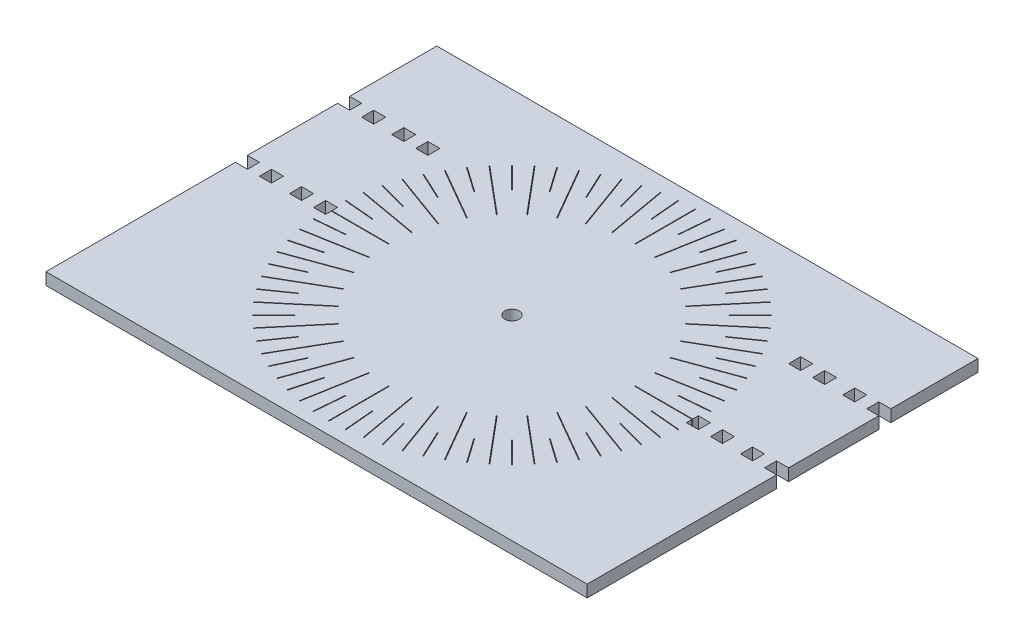
SolidWorks part; units mm, degrees
ref_plane "Front Plane" through (0, 0, 0) normal (0, 0, 1) x (1, 0, 0)
ref_plane "Top Plane" through (0, 0, 0) normal (0, 1, 0) x (1, 0, 0)
ref_plane "Right Plane" through (0, 0, 0) normal (1, 0, 0) x (0, 0, -1)
sketch "Sketch1" plane through (0, 0, 0) normal (0, 1, 0) x (1, 0, 0)
  line L0 (13.3728, 67.8735) -> (13.3728, -97.2265) construction
  line L1 (-100.9272, 67.8735) -> (127.6728, 67.8735)
  line L2 (-100.9272, 67.8735) -> (-100.9272, -97.2265)
  line L3 (-100.9272, -97.2265) -> (127.6728, -97.2265)
  line L4 (127.6728, 67.8735) -> (127.6728, -97.2265)
  line L5 (-100.9272, -14.6765) -> (127.6728, -14.6765) construction
  line L6 (-100.9272, -17.2165) -> (127.6728, -17.2165) construction
  line L7 (-100.9272, -12.1365) -> (127.6728, -12.1365) construction
  line L8 (-81.8772, 67.8735) -> (-81.8772, -97.2265) construction
  line L9 (108.6228, 67.8735) -> (108.6228, -97.2265) construction
  line L10 (-100.9272, 6.9135) -> (127.6728, 6.9135) construction
  line L11 (89.5728, -12.1365) -> (89.5728, -17.2165)
  line L12 (112.4328, -12.1365) -> (117.5128, -12.1365)
  line L13 (112.4328, -12.1365) -> (112.4328, -17.2165)
  line L14 (112.4328, -17.2165) -> (117.5128, -17.2165)
  line L15 (117.5128, -12.1365) -> (117.5128, -17.2165)
  line L16 (122.5928, -12.1365) -> (127.6728, -12.1365)
  line L17 (122.5928, -12.1365) -> (122.5928, -17.2165)
  line L18 (122.5928, -17.2165) -> (127.6728, -17.2165)
  line L19 (127.6728, -12.1365) -> (127.6728, -17.2165)
  line L20 (94.6528, -17.2165) -> (89.5728, -17.2165)
  line L21 (94.6528, -12.1365) -> (94.6528, -17.2165)
  line L22 (94.6528, -12.1365) -> (89.5728, -12.1365)
  line L23 (99.7328, -12.1365) -> (99.7328, -17.2165)
  line L24 (104.8128, -17.2165) -> (99.7328, -17.2165)
  line L25 (104.8128, -12.1365) -> (104.8128, -17.2165)
  line L26 (104.8128, -12.1365) -> (99.7328, -12.1365)
  line L27 (104.8128, 25.9635) -> (99.7328, 25.9635)
  line L28 (104.8128, 25.9635) -> (104.8128, 31.0435)
  line L29 (104.8128, 31.0435) -> (99.7328, 31.0435)
  line L30 (99.7328, 25.9635) -> (99.7328, 31.0435)
  line L31 (94.6528, 25.9635) -> (89.5728, 25.9635)
  line L32 (94.6528, 25.9635) -> (94.6528, 31.0435)
  line L33 (94.6528, 31.0435) -> (89.5728, 31.0435)
  line L34 (127.6728, 25.9635) -> (127.6728, 31.0435)
  line L35 (122.5928, 31.0435) -> (127.6728, 31.0435)
  line L36 (122.5928, 25.9635) -> (122.5928, 31.0435)
  line L37 (122.5928, 25.9635) -> (127.6728, 25.9635)
  line L38 (117.5128, 25.9635) -> (117.5128, 31.0435)
  line L39 (112.4328, 31.0435) -> (117.5128, 31.0435)
  line L40 (112.4328, 25.9635) -> (112.4328, 31.0435)
  line L41 (112.4328, 25.9635) -> (117.5128, 25.9635)
  line L42 (89.5728, 25.9635) -> (89.5728, 31.0435)
  line L43 (-78.0672, -12.1365) -> (-78.0672, -17.2165)
  line L44 (-100.9272, -12.1365) -> (-95.8472, -12.1365)
  line L45 (-100.9272, -12.1365) -> (-100.9272, -17.2165)
  line L46 (-100.9272, -17.2165) -> (-95.8472, -17.2165)
  line L47 (-95.8472, -12.1365) -> (-95.8472, -17.2165)
  line L48 (-90.7672, -12.1365) -> (-85.6872, -12.1365)
  line L49 (-90.7672, -12.1365) -> (-90.7672, -17.2165)
  line L50 (-90.7672, -17.2165) -> (-85.6872, -17.2165)
  line L51 (-85.6872, -12.1365) -> (-85.6872, -17.2165)
  line L52 (-72.9872, -17.2165) -> (-78.0672, -17.2165)
  line L53 (-72.9872, -12.1365) -> (-72.9872, -17.2165)
  line L54 (-72.9872, -12.1365) -> (-78.0672, -12.1365)
  line L55 (-67.9072, -12.1365) -> (-67.9072, -17.2165)
  line L56 (-62.8272, -17.2165) -> (-67.9072, -17.2165)
  line L57 (-62.8272, -12.1365) -> (-62.8272, -17.2165)
  line L58 (-62.8272, -12.1365) -> (-67.9072, -12.1365)
  line L59 (-62.8272, 25.9635) -> (-67.9072, 25.9635)
  line L60 (-62.8272, 25.9635) -> (-62.8272, 31.0435)
  line L61 (-62.8272, 31.0435) -> (-67.9072, 31.0435)
  line L62 (-67.9072, 25.9635) -> (-67.9072, 31.0435)
  line L63 (-72.9872, 25.9635) -> (-78.0672, 25.9635)
  line L64 (-72.9872, 25.9635) -> (-72.9872, 31.0435)
  line L65 (-72.9872, 31.0435) -> (-78.0672, 31.0435)
  line L66 (-85.6872, 25.9635) -> (-85.6872, 31.0435)
  line L67 (-90.7672, 31.0435) -> (-85.6872, 31.0435)
  line L68 (-90.7672, 25.9635) -> (-90.7672, 31.0435)
  line L69 (-90.7672, 25.9635) -> (-85.6872, 25.9635)
  line L70 (-95.8472, 25.9635) -> (-95.8472, 31.0435)
  line L71 (-100.9272, 31.0435) -> (-95.8472, 31.0435)
  line L72 (-100.9272, 25.9635) -> (-100.9272, 31.0435)
  line L73 (-100.9272, 25.9635) -> (-95.8472, 25.9635)
  line L74 (-78.0672, 25.9635) -> (-78.0672, 31.0435)
  circle A0 centre (13.3728, -14.6765) radius 3.048
  point P16 (13.3728, -14.6765)
  dimension "D8" = 6.096
  dimension "D1" = 228.6
  dimension "D2" = 165.1
  dimension "D7" = 19.05
  dimension "D9" = 5.08
  dimension "D10" = 3.81
  dimension "D11" = 5.08
  dimension "D12" = 5.08
  dimension "D13" = 5.08
  dimension "D14" = 5.08
  dimension "D15" = 3.81
  dimension "D16" = 5.08
  dimension "D3" = 2.54
  dimension "D4" = 2.54
  dimension "D5" = 95.25
  dimension "D6" = 95.25
extrude "Boss-Extrude1" add sketch "Sketch1" along normal blind 5.08 contours L73 L2 L44 L47 L46 L3 L4 L18 L17 L16 L37 L36 L35 L1 L71 L70 A0 L69 L68 L67 L66 L58 L57 L56 L55 L54 L53 L52 L43 L41 L40 L39 L38 L26 L25 L24 L23 L22 L21 L20
sketch "Sketch3" plane through (0, 5.08, 0) normal (0, 1, 0) x (1, 0, 0)
  line L0 (-62.8272, -14.6765) -> (89.5728, -14.6765) construction
  line L1 (-62.8272, -12.1365) -> (-62.8272, -17.2165) construction
  line L2 (89.5728, -12.1365) -> (89.5728, -17.2165) construction
  line L3 (13.3728, 67.8735) -> (13.3728, -97.2265) construction
  line L4 (-100.9272, 67.8735) -> (127.6728, 67.8735) construction
  line L5 (-100.9272, -97.2265) -> (127.6728, -97.2265) construction
  line L6 (77.9074, -20.1951) -> (90.5591, -21.3019)
  line L7 (78.1428, -14.5495) -> (90.8428, -14.5495)
  line L8 (78.1428, -14.5495) -> (78.1428, -14.8035)
  line L9 (78.1428, -14.8035) -> (90.8428, -14.8035)
  line L10 (90.8428, -14.5495) -> (90.8428, -14.8035)
  line L11 (77.9074, -20.1951) -> (77.8853, -20.4481)
  line L12 (77.8853, -20.4481) -> (90.537, -21.555)
  line L13 (90.5591, -21.3019) -> (90.537, -21.555)
  line L14 (77.1809, -25.7986) -> (89.688, -28.0039)
  line L15 (77.1809, -25.7986) -> (77.1368, -26.0488)
  line L16 (77.1368, -26.0488) -> (89.6439, -28.2541)
  line L17 (89.688, -28.0039) -> (89.6439, -28.2541)
  line L18 (75.9687, -31.3175) -> (88.236, -34.6045)
  line L19 (75.9687, -31.3175) -> (75.903, -31.5629)
  line L20 (75.903, -31.5629) -> (88.1703, -34.8499)
  line L21 (88.236, -34.6045) -> (88.1703, -34.8499)
  line L22 (74.2802, -36.7098) -> (86.2143, -41.0534)
  line L23 (74.2802, -36.7098) -> (74.1933, -36.9485)
  line L24 (74.1933, -36.9485) -> (86.1274, -41.2921)
  line L25 (86.2143, -41.0534) -> (86.1274, -41.2921)
  line L26 (72.1281, -41.9344) -> (83.6382, -47.3016)
  line L27 (72.1281, -41.9344) -> (72.0207, -42.1646)
  line L28 (72.0207, -42.1646) -> (83.5308, -47.5318)
  line L29 (83.6382, -47.3016) -> (83.5308, -47.5318)
  line L30 (69.5288, -46.9515) -> (80.5273, -53.3015)
  line L31 (69.5288, -46.9515) -> (69.4018, -47.1715)
  line L32 (69.4018, -47.1715) -> (80.4003, -53.5215)
  line L33 (80.5273, -53.3015) -> (80.4003, -53.5215)
  line L34 (66.5022, -51.723) -> (76.9054, -59.0074)
  line L35 (66.5022, -51.723) -> (66.3565, -51.9311)
  line L36 (66.3565, -51.9311) -> (76.7597, -59.2155)
  line L37 (76.9054, -59.0074) -> (76.7597, -59.2155)
  line L38 (63.0712, -56.2126) -> (72.7999, -64.376)
  line L39 (63.0712, -56.2126) -> (62.9079, -56.4071)
  line L40 (62.9079, -56.4071) -> (72.6367, -64.5705)
  line L41 (72.7999, -64.376) -> (72.6367, -64.5705)
  line L42 (59.262, -60.386) -> (68.2422, -69.3662)
  line L43 (59.262, -60.386) -> (59.0824, -60.5656)
  line L44 (59.0824, -60.5656) -> (68.0626, -69.5459)
  line L45 (68.2422, -69.3662) -> (68.0626, -69.5459)
  line L46 (55.1035, -64.2116) -> (63.2669, -73.9403)
  line L47 (55.1035, -64.2116) -> (54.9089, -64.3748)
  line L48 (54.9089, -64.3748) -> (63.0723, -74.1036)
  line L49 (63.2669, -73.9403) -> (63.0723, -74.1036)
  line L50 (50.6274, -67.6601) -> (57.9118, -78.0634)
  line L51 (50.6274, -67.6601) -> (50.4194, -67.8058)
  line L52 (50.4194, -67.8058) -> (57.7038, -78.209)
  line L53 (57.9118, -78.0634) -> (57.7038, -78.209)
  line L54 (45.8678, -70.7055) -> (52.2178, -81.704)
  line L55 (45.8678, -70.7055) -> (45.6479, -70.8325)
  line L56 (45.6479, -70.8325) -> (51.9979, -81.831)
  line L57 (52.2178, -81.704) -> (51.9979, -81.831)
  line L58 (40.8609, -73.3244) -> (46.2282, -84.8345)
  line L59 (40.8609, -73.3244) -> (40.6307, -73.4317)
  line L60 (40.6307, -73.4317) -> (45.998, -84.9418)
  line L61 (46.2282, -84.8345) -> (45.998, -84.9418)
  line L62 (35.6448, -75.4969) -> (39.9885, -87.431)
  line L63 (35.6448, -75.4969) -> (35.4062, -75.5838)
  line L64 (35.4062, -75.5838) -> (39.7498, -87.5179)
  line L65 (39.9885, -87.431) -> (39.7498, -87.5179)
  line L66 (30.2592, -77.2066) -> (33.5462, -89.4739)
  line L67 (30.2592, -77.2066) -> (30.0139, -77.2724)
  line L68 (30.0139, -77.2724) -> (33.3009, -89.5396)
  line L69 (33.5462, -89.4739) -> (33.3009, -89.5396)
  line L70 (24.7451, -78.4404) -> (26.9504, -90.9475)
  line L71 (24.7451, -78.4404) -> (24.495, -78.4845)
  line L72 (24.495, -78.4845) -> (26.7003, -90.9916)
  line L73 (26.9504, -90.9475) -> (26.7003, -90.9916)
  line L74 (19.1444, -79.189) -> (20.2513, -91.8406)
  line L75 (19.1444, -79.189) -> (18.8914, -79.2111)
  line L76 (18.8914, -79.2111) -> (19.9983, -91.8628)
  line L77 (20.2513, -91.8406) -> (19.9983, -91.8628)
  line L78 (13.4998, -79.4465) -> (13.4998, -92.1465)
  line L79 (13.4998, -79.4465) -> (13.2458, -79.4465)
  line L80 (13.2458, -79.4465) -> (13.2458, -92.1465)
  line L81 (13.4998, -92.1465) -> (13.2458, -92.1465)
  line L82 (7.8543, -79.2111) -> (6.7474, -91.8628)
  line L83 (7.8543, -79.2111) -> (7.6013, -79.189)
  line L84 (7.6013, -79.189) -> (6.4944, -91.8406)
  line L85 (6.7474, -91.8628) -> (6.4944, -91.8406)
  line L86 (2.2507, -78.4845) -> (0.0454, -90.9916)
  line L87 (2.2507, -78.4845) -> (2.0006, -78.4404)
  line L88 (2.0006, -78.4404) -> (-0.2047, -90.9475)
  line L89 (0.0454, -90.9916) -> (-0.2047, -90.9475)
  line L90 (-3.2682, -77.2724) -> (-6.5552, -89.5396)
  line L91 (-3.2682, -77.2724) -> (-3.5135, -77.2066)
  line L92 (-3.5135, -77.2066) -> (-6.8005, -89.4739)
  line L93 (-6.5552, -89.5396) -> (-6.8005, -89.4739)
  line L94 (-8.6605, -75.5838) -> (-13.0041, -87.5179)
  line L95 (-8.6605, -75.5838) -> (-8.8991, -75.4969)
  line L96 (-8.8991, -75.4969) -> (-13.2428, -87.431)
  line L97 (-13.0041, -87.5179) -> (-13.2428, -87.431)
  line L98 (-13.885, -73.4317) -> (-19.2523, -84.9418)
  line L99 (-13.885, -73.4317) -> (-14.1152, -73.3244)
  line L100 (-14.1152, -73.3244) -> (-19.4825, -84.8345)
  line L101 (-19.2523, -84.9418) -> (-19.4825, -84.8345)
  line L102 (-18.9022, -70.8325) -> (-25.2522, -81.831)
  line L103 (-18.9022, -70.8325) -> (-19.1221, -70.7055)
  line L104 (-19.1221, -70.7055) -> (-25.4721, -81.704)
  line L105 (-25.2522, -81.831) -> (-25.4721, -81.704)
  line L106 (-23.6737, -67.8058) -> (-30.9581, -78.209)
  line L107 (-23.6737, -67.8058) -> (-23.8817, -67.6601)
  line L108 (-23.8817, -67.6601) -> (-31.1662, -78.0634)
  line L109 (-30.9581, -78.209) -> (-31.1662, -78.0634)
  line L110 (-28.1632, -64.3748) -> (-36.3266, -74.1036)
  line L111 (-28.1632, -64.3748) -> (-28.3578, -64.2116)
  line L112 (-28.3578, -64.2116) -> (-36.5212, -73.9403)
  line L113 (-36.3266, -74.1036) -> (-36.5212, -73.9403)
  line L114 (-32.3367, -60.5656) -> (-41.3169, -69.5459)
  line L115 (-32.3367, -60.5656) -> (-32.5163, -60.386)
  line L116 (-32.5163, -60.386) -> (-41.4965, -69.3662)
  line L117 (-41.3169, -69.5459) -> (-41.4965, -69.3662)
  line L118 (-36.1622, -56.4071) -> (-45.891, -64.5705)
  line L119 (-36.1622, -56.4071) -> (-36.3255, -56.2126)
  line L120 (-36.3255, -56.2126) -> (-46.0542, -64.376)
  line L121 (-45.891, -64.5705) -> (-46.0542, -64.376)
  line L122 (-39.6108, -51.9311) -> (-50.014, -59.2155)
  line L123 (-39.6108, -51.9311) -> (-39.7565, -51.723)
  line L124 (-39.7565, -51.723) -> (-50.1597, -59.0074)
  line L125 (-50.014, -59.2155) -> (-50.1597, -59.0074)
  line L126 (-42.6561, -47.1715) -> (-53.6546, -53.5215)
  line L127 (-42.6561, -47.1715) -> (-42.7831, -46.9515)
  line L128 (-42.7831, -46.9515) -> (-53.7816, -53.3015)
  line L129 (-53.6546, -53.5215) -> (-53.7816, -53.3015)
  line L130 (-45.275, -42.1646) -> (-56.7851, -47.5318)
  line L131 (-45.275, -42.1646) -> (-45.3824, -41.9344)
  line L132 (-45.3824, -41.9344) -> (-56.8925, -47.3016)
  line L133 (-56.7851, -47.5318) -> (-56.8925, -47.3016)
  line L134 (-47.4476, -36.9485) -> (-59.3817, -41.2921)
  line L135 (-47.4476, -36.9485) -> (-47.5345, -36.7098)
  line L136 (-47.5345, -36.7098) -> (-59.4686, -41.0534)
  line L137 (-59.3817, -41.2921) -> (-59.4686, -41.0534)
  line L138 (-49.1573, -31.5629) -> (-61.4246, -34.8499)
  line L139 (-49.1573, -31.5629) -> (-49.223, -31.3175)
  line L140 (-49.223, -31.3175) -> (-61.4903, -34.6045)
  line L141 (-61.4246, -34.8499) -> (-61.4903, -34.6045)
  line L142 (-50.3911, -26.0488) -> (-62.8982, -28.2541)
  line L143 (-50.3911, -26.0488) -> (-50.4352, -25.7986)
  line L144 (-50.4352, -25.7986) -> (-62.9423, -28.0039)
  line L145 (-62.8982, -28.2541) -> (-62.9423, -28.0039)
  line L146 (-51.1396, -20.4481) -> (-63.7913, -21.555)
  line L147 (-51.1396, -20.4481) -> (-51.1618, -20.1951)
  line L148 (-51.1618, -20.1951) -> (-63.8134, -21.3019)
  line L149 (-63.7913, -21.555) -> (-63.8134, -21.3019)
  line L150 (-51.3972, -14.8035) -> (-64.0972, -14.8035)
  line L151 (-51.3972, -14.8035) -> (-51.3972, -14.5495)
  line L152 (-51.3972, -14.5495) -> (-64.0972, -14.5495)
  line L153 (-64.0972, -14.8035) -> (-64.0972, -14.5495)
  line L154 (-51.1618, -9.1579) -> (-63.8134, -8.0511)
  line L155 (-51.1618, -9.1579) -> (-51.1396, -8.9049)
  line L156 (-51.1396, -8.9049) -> (-63.7913, -7.798)
  line L157 (-63.8134, -8.0511) -> (-63.7913, -7.798)
  line L158 (-50.4352, -3.5544) -> (-62.9423, -1.349)
  line L159 (-50.4352, -3.5544) -> (-50.3911, -3.3042)
  line L160 (-50.3911, -3.3042) -> (-62.8982, -1.0989)
  line L161 (-62.9423, -1.349) -> (-62.8982, -1.0989)
  line L162 (-49.223, 1.9645) -> (-61.4903, 5.2515)
  line L163 (-49.223, 1.9645) -> (-49.1573, 2.2099)
  line L164 (-49.1573, 2.2099) -> (-61.4246, 5.4969)
  line L165 (-61.4903, 5.2515) -> (-61.4246, 5.4969)
  line L166 (-47.5345, 7.3568) -> (-59.4686, 11.7005)
  line L167 (-47.5345, 7.3568) -> (-47.4476, 7.5955)
  line L168 (-47.4476, 7.5955) -> (-59.3817, 11.9392)
  line L169 (-59.4686, 11.7005) -> (-59.3817, 11.9392)
  line L170 (-45.3824, 12.5814) -> (-56.8925, 17.9486)
  line L171 (-45.3824, 12.5814) -> (-45.275, 12.8116)
  line L172 (-45.275, 12.8116) -> (-56.7851, 18.1788)
  line L173 (-56.8925, 17.9486) -> (-56.7851, 18.1788)
  line L174 (-42.7831, 17.5985) -> (-53.7816, 23.9485)
  line L175 (-42.7831, 17.5985) -> (-42.6561, 17.8185)
  line L176 (-42.6561, 17.8185) -> (-53.6546, 24.1685)
  line L177 (-53.7816, 23.9485) -> (-53.6546, 24.1685)
  line L178 (-39.7565, 22.37) -> (-50.1597, 29.6544)
  line L179 (-39.7565, 22.37) -> (-39.6108, 22.5781)
  line L180 (-39.6108, 22.5781) -> (-50.014, 29.8625)
  line L181 (-50.1597, 29.6544) -> (-50.014, 29.8625)
  line L182 (-36.3255, 26.8596) -> (-46.0542, 35.023)
  line L183 (-36.3255, 26.8596) -> (-36.1622, 27.0542)
  line L184 (-36.1622, 27.0542) -> (-45.891, 35.2176)
  line L185 (-46.0542, 35.023) -> (-45.891, 35.2176)
  line L186 (-32.5163, 31.033) -> (-41.4965, 40.0133)
  line L187 (-32.5163, 31.033) -> (-32.3367, 31.2126)
  line L188 (-32.3367, 31.2126) -> (-41.3169, 40.1929)
  line L189 (-41.4965, 40.0133) -> (-41.3169, 40.1929)
  line L190 (-28.3578, 34.8586) -> (-36.5212, 44.5873)
  line L191 (-28.3578, 34.8586) -> (-28.1632, 35.0218)
  line L192 (-28.1632, 35.0218) -> (-36.3266, 44.7506)
  line L193 (-36.5212, 44.5873) -> (-36.3266, 44.7506)
  line L194 (-23.8817, 38.3071) -> (-31.1662, 48.7104)
  line L195 (-23.8817, 38.3071) -> (-23.6737, 38.4528)
  line L196 (-23.6737, 38.4528) -> (-30.9581, 48.8561)
  line L197 (-31.1662, 48.7104) -> (-30.9581, 48.8561)
  line L198 (-19.1221, 41.3525) -> (-25.4721, 52.351)
  line L199 (-19.1221, 41.3525) -> (-18.9022, 41.4795)
  line L200 (-18.9022, 41.4795) -> (-25.2522, 52.478)
  line L201 (-25.4721, 52.351) -> (-25.2522, 52.478)
  line L202 (-14.1152, 43.9714) -> (-19.4825, 55.4815)
  line L203 (-14.1152, 43.9714) -> (-13.885, 44.0787)
  line L204 (-13.885, 44.0787) -> (-19.2523, 55.5888)
  line L205 (-19.4825, 55.4815) -> (-19.2523, 55.5888)
  line L206 (-8.8991, 46.144) -> (-13.2428, 58.0781)
  line L207 (-8.8991, 46.144) -> (-8.6605, 46.2308)
  line L208 (-8.6605, 46.2308) -> (-13.0041, 58.1649)
  line L209 (-13.2428, 58.0781) -> (-13.0041, 58.1649)
  line L210 (-3.5135, 47.8537) -> (-6.8005, 60.1209)
  line L211 (-3.5135, 47.8537) -> (-3.2682, 47.9194)
  line L212 (-3.2682, 47.9194) -> (-6.5552, 60.1867)
  line L213 (-6.8005, 60.1209) -> (-6.5552, 60.1867)
  line L214 (2.0006, 49.0875) -> (-0.2047, 61.5945)
  line L215 (2.0006, 49.0875) -> (2.2507, 49.1316)
  line L216 (2.2507, 49.1316) -> (0.0454, 61.6386)
  line L217 (-0.2047, 61.5945) -> (0.0454, 61.6386)
  line L218 (7.6013, 49.836) -> (6.4944, 62.4876)
  line L219 (7.6013, 49.836) -> (7.8543, 49.8581)
  line L220 (7.8543, 49.8581) -> (6.7474, 62.5098)
  line L221 (6.4944, 62.4876) -> (6.7474, 62.5098)
  line L222 (13.2458, 50.0935) -> (13.2458, 62.7935)
  line L223 (13.2458, 50.0935) -> (13.4998, 50.0935)
  line L224 (13.4998, 50.0935) -> (13.4998, 62.7935)
  line L225 (13.2458, 62.7935) -> (13.4998, 62.7935)
  line L226 (18.8914, 49.8581) -> (19.9983, 62.5098)
  line L227 (18.8914, 49.8581) -> (19.1444, 49.836)
  line L228 (19.1444, 49.836) -> (20.2513, 62.4876)
  line L229 (19.9983, 62.5098) -> (20.2513, 62.4876)
  line L230 (24.495, 49.1316) -> (26.7003, 61.6386)
  line L231 (24.495, 49.1316) -> (24.7451, 49.0875)
  line L232 (24.7451, 49.0875) -> (26.9504, 61.5945)
  line L233 (26.7003, 61.6386) -> (26.9504, 61.5945)
  line L234 (30.0139, 47.9194) -> (33.3009, 60.1867)
  line L235 (30.0139, 47.9194) -> (30.2592, 47.8537)
  line L236 (30.2592, 47.8537) -> (33.5462, 60.1209)
  line L237 (33.3009, 60.1867) -> (33.5462, 60.1209)
  line L238 (35.4062, 46.2308) -> (39.7498, 58.1649)
  line L239 (35.4062, 46.2308) -> (35.6448, 46.144)
  line L240 (35.6448, 46.144) -> (39.9885, 58.0781)
  line L241 (39.7498, 58.1649) -> (39.9885, 58.0781)
  line L242 (40.6307, 44.0787) -> (45.998, 55.5888)
  line L243 (40.6307, 44.0787) -> (40.8609, 43.9714)
  line L244 (40.8609, 43.9714) -> (46.2282, 55.4815)
  line L245 (45.998, 55.5888) -> (46.2282, 55.4815)
  line L246 (45.6479, 41.4795) -> (51.9979, 52.478)
  line L247 (45.6479, 41.4795) -> (45.8678, 41.3525)
  line L248 (45.8678, 41.3525) -> (52.2178, 52.351)
  line L249 (51.9979, 52.478) -> (52.2178, 52.351)
  line L250 (50.4194, 38.4528) -> (57.7038, 48.8561)
  line L251 (50.4194, 38.4528) -> (50.6274, 38.3071)
  line L252 (50.6274, 38.3071) -> (57.9118, 48.7104)
  line L253 (57.7038, 48.8561) -> (57.9118, 48.7104)
  line L254 (54.9089, 35.0218) -> (63.0723, 44.7506)
  line L255 (54.9089, 35.0218) -> (55.1035, 34.8586)
  line L256 (55.1035, 34.8586) -> (63.2669, 44.5873)
  line L257 (63.0723, 44.7506) -> (63.2669, 44.5873)
  line L258 (59.0824, 31.2126) -> (68.0626, 40.1929)
  line L259 (59.0824, 31.2126) -> (59.262, 31.033)
  line L260 (59.262, 31.033) -> (68.2422, 40.0133)
  line L261 (68.0626, 40.1929) -> (68.2422, 40.0133)
  line L262 (62.9079, 27.0542) -> (72.6367, 35.2176)
  line L263 (62.9079, 27.0542) -> (63.0712, 26.8596)
  line L264 (63.0712, 26.8596) -> (72.7999, 35.023)
  line L265 (72.6367, 35.2176) -> (72.7999, 35.023)
  line L266 (66.3565, 22.5781) -> (76.7597, 29.8625)
  line L267 (66.3565, 22.5781) -> (66.5022, 22.37)
  line L268 (66.5022, 22.37) -> (76.9054, 29.6544)
  line L269 (76.7597, 29.8625) -> (76.9054, 29.6544)
  line L270 (69.4018, 17.8185) -> (80.4003, 24.1685)
  line L271 (69.4018, 17.8185) -> (69.5288, 17.5985)
  line L272 (69.5288, 17.5985) -> (80.5273, 23.9485)
  line L273 (80.4003, 24.1685) -> (80.5273, 23.9485)
  line L274 (72.0207, 12.8116) -> (83.5308, 18.1788)
  line L275 (72.0207, 12.8116) -> (72.1281, 12.5814)
  line L276 (72.1281, 12.5814) -> (83.6382, 17.9486)
  line L277 (83.5308, 18.1788) -> (83.6382, 17.9486)
  line L278 (74.1933, 7.5955) -> (86.1274, 11.9392)
  line L279 (74.1933, 7.5955) -> (74.2802, 7.3568)
  line L280 (74.2802, 7.3568) -> (86.2143, 11.7005)
  line L281 (86.1274, 11.9392) -> (86.2143, 11.7005)
  line L282 (75.903, 2.2099) -> (88.1703, 5.4969)
  line L283 (75.903, 2.2099) -> (75.9687, 1.9645)
  line L284 (75.9687, 1.9645) -> (88.236, 5.2515)
  line L285 (88.1703, 5.4969) -> (88.236, 5.2515)
  line L286 (77.1368, -3.3042) -> (89.6439, -1.0989)
  line L287 (77.1368, -3.3042) -> (77.1809, -3.5544)
  line L288 (77.1809, -3.5544) -> (89.688, -1.349)
  line L289 (89.6439, -1.0989) -> (89.688, -1.349)
  line L290 (77.8853, -8.9049) -> (90.537, -7.798)
  line L291 (77.8853, -8.9049) -> (77.9074, -9.1579)
  line L292 (77.9074, -9.1579) -> (90.5591, -8.0511)
  line L293 (90.537, -7.798) -> (90.5591, -8.0511)
  point P16 (13.3728, -14.6765)
  point P17 (78.1428, -14.6765)
  point P273 (13.3728, -14.6765)
  dimension "D1" = 0.254
  dimension "D2" = 0.127
  dimension "D3" = 64.77
  dimension "D4" = 12.7
  dimension "D5" = 72
extrude "Cut-Extrude1" cut sketch "Sketch3" against normal blind 5.08
sketch "Sketch4" plane through (0, 5.08, 0) normal (0, 1, 0) x (1, 0, 0)
  line L0 (13.3728, 67.8735) -> (13.3728, -97.2265) construction
  line L1 (-100.9272, 67.8735) -> (127.6728, 67.8735) construction
  line L2 (-100.9272, -97.2265) -> (127.6728, -97.2265) construction
  line L3 (-67.9072, -14.6765) -> (94.6528, -14.6765) construction
  line L4 (-67.9072, -12.1365) -> (-67.9072, -17.2165) construction
  line L5 (94.6528, -12.1365) -> (94.6528, -17.2165) construction
  line L6 (64.6738, -23.5933) -> (89.688, -28.0039)
  line L7 (65.4428, -14.5495) -> (90.8428, -14.5495)
  line L8 (65.4428, -14.5495) -> (65.4428, -14.8035)
  line L9 (65.4428, -14.8035) -> (90.8428, -14.8035)
  line L10 (90.8428, -14.5495) -> (90.8428, -14.8035)
  line L11 (64.6738, -23.5933) -> (64.6297, -23.8434)
  line L12 (64.6297, -23.8434) -> (89.6439, -28.2541)
  line L13 (89.688, -28.0039) -> (89.6439, -28.2541)
  line L14 (62.3461, -32.3661) -> (86.2143, -41.0534)
  line L15 (62.3461, -32.3661) -> (62.2592, -32.6048)
  line L16 (62.2592, -32.6048) -> (86.1274, -41.2921)
  line L17 (86.2143, -41.0534) -> (86.1274, -41.2921)
  line L18 (58.5303, -40.6015) -> (80.5273, -53.3015)
  line L19 (58.5303, -40.6015) -> (58.4033, -40.8215)
  line L20 (58.4033, -40.8215) -> (80.4003, -53.5215)
  line L21 (80.5273, -53.3015) -> (80.4003, -53.5215)
  line L22 (53.3424, -48.0492) -> (72.7999, -64.376)
  line L23 (53.3424, -48.0492) -> (53.1791, -48.2437)
  line L24 (53.1791, -48.2437) -> (72.6367, -64.5705)
  line L25 (72.7999, -64.376) -> (72.6367, -64.5705)
  line L26 (46.9401, -54.4828) -> (63.2669, -73.9403)
  line L27 (46.9401, -54.4828) -> (46.7455, -54.6461)
  line L28 (46.7455, -54.6461) -> (63.0723, -74.1036)
  line L29 (63.2669, -73.9403) -> (63.0723, -74.1036)
  line L30 (39.5178, -59.7069) -> (52.2178, -81.704)
  line L31 (39.5178, -59.7069) -> (39.2979, -59.8339)
  line L32 (39.2979, -59.8339) -> (51.9979, -81.831)
  line L33 (52.2178, -81.704) -> (51.9979, -81.831)
  line L34 (31.3012, -63.5628) -> (39.9885, -87.431)
  line L35 (31.3012, -63.5628) -> (31.0625, -63.6497)
  line L36 (31.0625, -63.6497) -> (39.7498, -87.5179)
  line L37 (39.9885, -87.431) -> (39.7498, -87.5179)
  line L38 (22.5398, -65.9334) -> (26.9504, -90.9475)
  line L39 (22.5398, -65.9334) -> (22.2896, -65.9775)
  line L40 (22.2896, -65.9775) -> (26.7003, -90.9916)
  line L41 (26.9504, -90.9475) -> (26.7003, -90.9916)
  line L42 (13.4998, -66.7465) -> (13.4998, -92.1465)
  line L43 (13.4998, -66.7465) -> (13.2458, -66.7465)
  line L44 (13.2458, -66.7465) -> (13.2458, -92.1465)
  line L45 (13.4998, -92.1465) -> (13.2458, -92.1465)
  line L46 (4.4561, -65.9775) -> (0.0454, -90.9916)
  line L47 (4.4561, -65.9775) -> (4.2059, -65.9334)
  line L48 (4.2059, -65.9334) -> (-0.2047, -90.9475)
  line L49 (0.0454, -90.9916) -> (-0.2047, -90.9475)
  line L50 (-4.3168, -63.6497) -> (-13.0041, -87.5179)
  line L51 (-4.3168, -63.6497) -> (-4.5555, -63.5628)
  line L52 (-4.5555, -63.5628) -> (-13.2428, -87.431)
  line L53 (-13.0041, -87.5179) -> (-13.2428, -87.431)
  line L54 (-12.5522, -59.8339) -> (-25.2522, -81.831)
  line L55 (-12.5522, -59.8339) -> (-12.7721, -59.7069)
  line L56 (-12.7721, -59.7069) -> (-25.4721, -81.704)
  line L57 (-25.2522, -81.831) -> (-25.4721, -81.704)
  line L58 (-19.9998, -54.6461) -> (-36.3266, -74.1036)
  line L59 (-19.9998, -54.6461) -> (-20.1944, -54.4828)
  line L60 (-20.1944, -54.4828) -> (-36.5212, -73.9403)
  line L61 (-36.3266, -74.1036) -> (-36.5212, -73.9403)
  line L62 (-26.4335, -48.2437) -> (-45.891, -64.5705)
  line L63 (-26.4335, -48.2437) -> (-26.5967, -48.0492)
  line L64 (-26.5967, -48.0492) -> (-46.0542, -64.376)
  line L65 (-45.891, -64.5705) -> (-46.0542, -64.376)
  line L66 (-31.6576, -40.8215) -> (-53.6546, -53.5215)
  line L67 (-31.6576, -40.8215) -> (-31.7846, -40.6015)
  line L68 (-31.7846, -40.6015) -> (-53.7816, -53.3015)
  line L69 (-53.6546, -53.5215) -> (-53.7816, -53.3015)
  line L70 (-35.5135, -32.6048) -> (-59.3817, -41.2921)
  line L71 (-35.5135, -32.6048) -> (-35.6004, -32.3661)
  line L72 (-35.6004, -32.3661) -> (-59.4686, -41.0534)
  line L73 (-59.3817, -41.2921) -> (-59.4686, -41.0534)
  line L74 (-37.884, -23.8434) -> (-62.8982, -28.2541)
  line L75 (-37.884, -23.8434) -> (-37.9281, -23.5933)
  line L76 (-37.9281, -23.5933) -> (-62.9423, -28.0039)
  line L77 (-62.8982, -28.2541) -> (-62.9423, -28.0039)
  line L78 (-38.6972, -14.8035) -> (-64.0972, -14.8035)
  line L79 (-38.6972, -14.8035) -> (-38.6972, -14.5495)
  line L80 (-38.6972, -14.5495) -> (-64.0972, -14.5495)
  line L81 (-64.0972, -14.8035) -> (-64.0972, -14.5495)
  line L82 (-37.9281, -5.7597) -> (-62.9423, -1.349)
  line L83 (-37.9281, -5.7597) -> (-37.884, -5.5096)
  line L84 (-37.884, -5.5096) -> (-62.8982, -1.0989)
  line L85 (-62.9423, -1.349) -> (-62.8982, -1.0989)
  line L86 (-35.6004, 3.0132) -> (-59.4686, 11.7005)
  line L87 (-35.6004, 3.0132) -> (-35.5135, 3.2518)
  line L88 (-35.5135, 3.2518) -> (-59.3817, 11.9392)
  line L89 (-59.4686, 11.7005) -> (-59.3817, 11.9392)
  line L90 (-31.7846, 11.2485) -> (-53.7816, 23.9485)
  line L91 (-31.7846, 11.2485) -> (-31.6576, 11.4685)
  line L92 (-31.6576, 11.4685) -> (-53.6546, 24.1685)
  line L93 (-53.7816, 23.9485) -> (-53.6546, 24.1685)
  line L94 (-26.5967, 18.6962) -> (-46.0542, 35.023)
  line L95 (-26.5967, 18.6962) -> (-26.4335, 18.8907)
  line L96 (-26.4335, 18.8907) -> (-45.891, 35.2176)
  line L97 (-46.0542, 35.023) -> (-45.891, 35.2176)
  line L98 (-20.1944, 25.1298) -> (-36.5212, 44.5873)
  line L99 (-20.1944, 25.1298) -> (-19.9998, 25.2931)
  line L100 (-19.9998, 25.2931) -> (-36.3266, 44.7506)
  line L101 (-36.5212, 44.5873) -> (-36.3266, 44.7506)
  line L102 (-12.7721, 30.354) -> (-25.4721, 52.351)
  line L103 (-12.7721, 30.354) -> (-12.5522, 30.481)
  line L104 (-12.5522, 30.481) -> (-25.2522, 52.478)
  line L105 (-25.4721, 52.351) -> (-25.2522, 52.478)
  line L106 (-4.5555, 34.2099) -> (-13.2428, 58.0781)
  line L107 (-4.5555, 34.2099) -> (-4.3168, 34.2967)
  line L108 (-4.3168, 34.2967) -> (-13.0041, 58.1649)
  line L109 (-13.2428, 58.0781) -> (-13.0041, 58.1649)
  line L110 (4.2059, 36.5804) -> (-0.2047, 61.5945)
  line L111 (4.2059, 36.5804) -> (4.4561, 36.6245)
  line L112 (4.4561, 36.6245) -> (0.0454, 61.6386)
  line L113 (-0.2047, 61.5945) -> (0.0454, 61.6386)
  line L114 (13.2458, 37.3935) -> (13.2458, 62.7935)
  line L115 (13.2458, 37.3935) -> (13.4998, 37.3935)
  line L116 (13.4998, 37.3935) -> (13.4998, 62.7935)
  line L117 (13.2458, 62.7935) -> (13.4998, 62.7935)
  line L118 (22.2896, 36.6245) -> (26.7003, 61.6386)
  line L119 (22.2896, 36.6245) -> (22.5398, 36.5804)
  line L120 (22.5398, 36.5804) -> (26.9504, 61.5945)
  line L121 (26.7003, 61.6386) -> (26.9504, 61.5945)
  line L122 (31.0625, 34.2967) -> (39.7498, 58.1649)
  line L123 (31.0625, 34.2967) -> (31.3012, 34.2099)
  line L124 (31.3012, 34.2099) -> (39.9885, 58.0781)
  line L125 (39.7498, 58.1649) -> (39.9885, 58.0781)
  line L126 (39.2979, 30.481) -> (51.9979, 52.478)
  line L127 (39.2979, 30.481) -> (39.5178, 30.354)
  line L128 (39.5178, 30.354) -> (52.2178, 52.351)
  line L129 (51.9979, 52.478) -> (52.2178, 52.351)
  line L130 (46.7455, 25.2931) -> (63.0723, 44.7506)
  line L131 (46.7455, 25.2931) -> (46.9401, 25.1298)
  line L132 (46.9401, 25.1298) -> (63.2669, 44.5873)
  line L133 (63.0723, 44.7506) -> (63.2669, 44.5873)
  line L134 (53.1791, 18.8907) -> (72.6367, 35.2176)
  line L135 (53.1791, 18.8907) -> (53.3424, 18.6962)
  line L136 (53.3424, 18.6962) -> (72.7999, 35.023)
  line L137 (72.6367, 35.2176) -> (72.7999, 35.023)
  line L138 (58.4033, 11.4685) -> (80.4003, 24.1685)
  line L139 (58.4033, 11.4685) -> (58.5303, 11.2485)
  line L140 (58.5303, 11.2485) -> (80.5273, 23.9485)
  line L141 (80.4003, 24.1685) -> (80.5273, 23.9485)
  line L142 (62.2592, 3.2518) -> (86.1274, 11.9392)
  line L143 (62.2592, 3.2518) -> (62.3461, 3.0132)
  line L144 (62.3461, 3.0132) -> (86.2143, 11.7005)
  line L145 (86.1274, 11.9392) -> (86.2143, 11.7005)
  line L146 (64.6297, -5.5096) -> (89.6439, -1.0989)
  line L147 (64.6297, -5.5096) -> (64.6738, -5.7597)
  line L148 (64.6738, -5.7597) -> (89.688, -1.349)
  line L149 (89.6439, -1.0989) -> (89.688, -1.349)
  point P12 (13.3728, -14.6765)
  point P161 (13.3728, -14.6765)
  dimension "D1" = 0.254
  dimension "D2" = 0.127
  dimension "D3" = 52.07
  dimension "D4" = 25.4
  dimension "D5" = 36
extrude "Cut-Extrude2" cut sketch "Sketch4" against normal blind 5.08
sketch "Sketch5" plane through (0, 5.08, 0) normal (0, 1, 0) x (1, 0, 0)
  line L0 (-95.8472, -14.6765) -> (122.5928, -14.6765)
  line L1 (-95.8472, -12.1365) -> (-95.8472, -17.2165) construction
  line L2 (122.5928, -12.1365) -> (122.5928, -17.2165) construction
  line L3 (13.3728, 67.8735) -> (13.3728, -97.2265)
  line L4 (-100.9272, 67.8735) -> (127.6728, 67.8735) construction
  line L5 (-100.9272, -97.2265) -> (127.6728, -97.2265) construction
